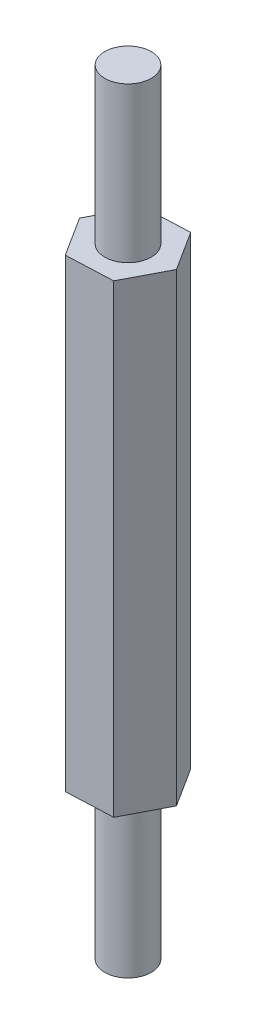
SolidWorks part; units mm, degrees
ref_plane "Front Plane" through (0, 0, 0) normal (0, 0, 1) x (1, 0, 0)
ref_plane "Top Plane" through (0, 0, 0) normal (0, 1, 0) x (1, 0, 0)
ref_plane "Right Plane" through (0, 0, 0) normal (1, 0, 0) x (0, 0, -1)
sketch "Sketch3" plane through (0, 0, 0) normal (0, 1, 0) x (1, 0, 0)
  line L1 (1.389, 2.6622) -> (-1.611, 2.534)
  line L2 (-1.611, 2.534) -> (-3, -0.1282)
  line L3 (-3, -0.1282) -> (-1.389, -2.6622)
  line L4 (-1.389, -2.6622) -> (1.611, -2.534)
  line L5 (1.611, -2.534) -> (3, 0.1282)
  line L6 (3, 0.1282) -> (1.389, 2.6622)
  circle A0 centre (0, 0) radius 2.6004 construction
  dimension "D2" = 5.2009
  dimension "D1" = 6
extrude "Boss-Extrude1" add sketch "Sketch3" along normal blind 30
sketch "Sketch4" plane through (0, 30, 0) normal (0, 1, 0) x (1, 0, 0)
  circle A0 centre (0, 0) radius 1.5
  dimension "D1" = 3
extrude "Boss-Extrude2" add sketch "Sketch4" along normal blind 10
sketch "Sketch5" plane through (0, 0, 0) normal (0, -1, 0) x (1, 0, 0)
  circle A0 centre (0, 0) radius 1.5
  dimension "D1" = 3
extrude "Boss-Extrude3" add sketch "Sketch5" along normal blind 10
